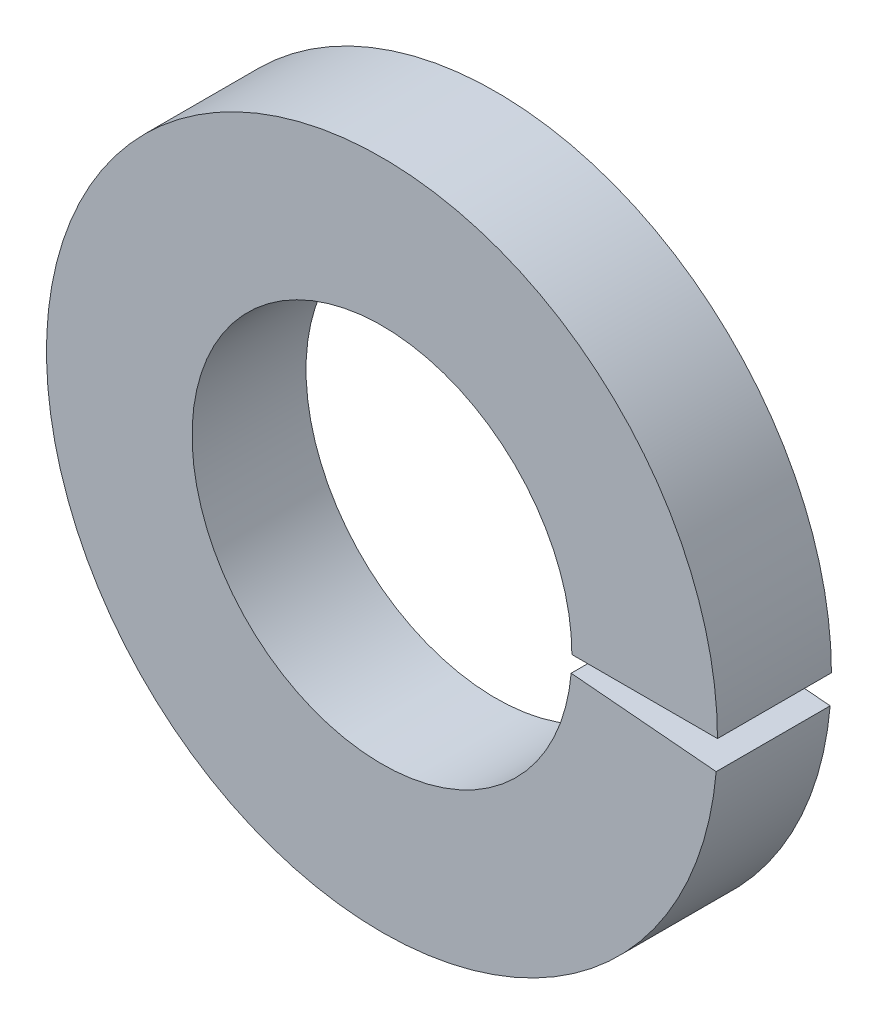
SolidWorks part; units mm, degrees
ref_plane "前视基准面" through (0, 0, 0) normal (0, 0, 1) x (1, 0, 0)
ref_plane "上视基准面" through (0, 0, 0) normal (0, 1, 0) x (1, 0, 0)
ref_plane "右视基准面" through (0, 0, 0) normal (1, 0, 0) x (0, 0, -1)
sketch "草图1" plane through (0, 0, 0) normal (0, 0, 1) x (1, 0, 0)
  line L0 (0, 0) -> (2.65, 0) construction
  line L1 (0, 0) -> (2.6399, -0.231) construction
  line L2 (1.4943, -0.1307) -> (2.6399, -0.231)
  line L3 (1.5, 0) -> (2.65, 0)
  circle A1 centre (0, 0) radius 1.5 construction
  circle A2 centre (0, 0) radius 2.65 construction
  arc A3 (1.5, 0) -> (1.4943, -0.1307) centre (0, 0) ccw
  arc A4 (2.65, 0) -> (2.6399, -0.231) centre (0, 0) ccw
  dimension "D1" = 5
extrude "凸台-拉伸1" add sketch "草图1" along normal blind 0.9 contours L3 A4 L2 A3
